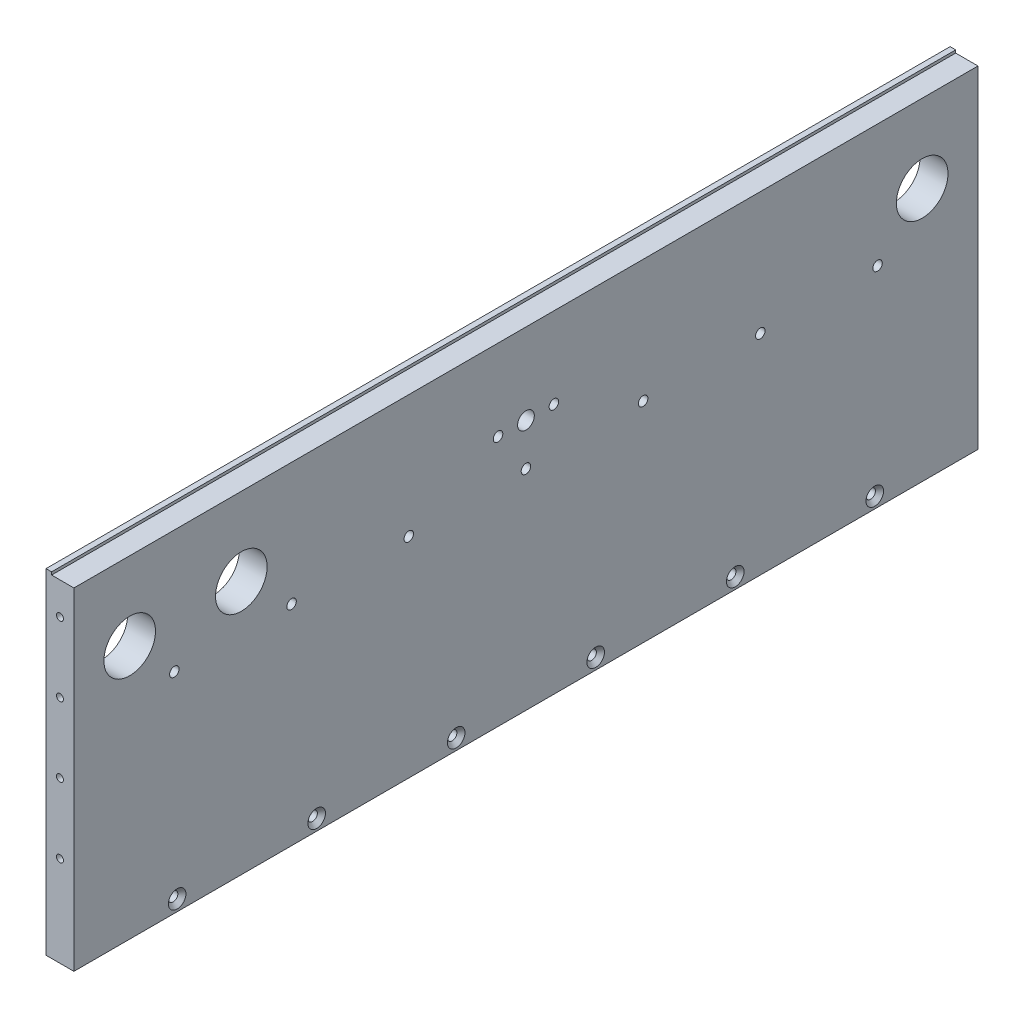
SolidWorks part; units mm, degrees
ref_plane "Front Plane" through (0, 0, 0) normal (0, 0, 1) x (1, 0, 0)
ref_plane "Top Plane" through (0, 0, 0) normal (0, 1, 0) x (1, 0, 0)
ref_plane "Right Plane" through (0, 0, 0) normal (1, 0, 0) x (0, 0, -1)
sketch "Sketch1" plane through (0, 0, 0) normal (1, 0, 0) x (0, 0, -1)
  line L1 (162, -20) -> (-162, -20)
  line L2 (162, -20) -> (162, 20)
  line L3 (162, 20) -> (-162, 20)
  line L4 (-162, -20) -> (-162, 20)
  line L5 (162, -20) -> (-162, 20) construction
  line L6 (162, 20) -> (-162, -20) construction
  point P0 (0, 0)
  dimension "D1" = 40
  dimension "D2" = 324
extrude "Boss-Extrude1" add sketch "Sketch1" along normal blind 10
sketch "Sketch2" plane through (0, 0, 0) normal (-1, 0, 0) x (0, 0, 1)
  line L0 (0, -20) -> (0, -10) construction
  line L1 (162, -20) -> (-162, -20) construction
  line L2 (-10, -20) -> (-10, -10) construction
  point P6 (0, -10)
  point P9 (-10, -10)
  dimension "D1" = 10
  dimension "D2" = 10
  dimension "D3" = 10
hole_wizard "G1/4 Tapped Hole1" positions "3DSketch1" profile "Sketch4" tap size "G1/4" standard "DIN" end condition through all
sketch3d "3DSketch1"
  point P0 (0, -10, 0)
sketch "Sketch4" plane through (0, -10, 0) normal (0, 1, 0) x (0, 0, 1)
  line L0 (0, 0) -> (0, 10)
  line L1 (0, 10) -> (3, 10)
  line L2 (3, 10) -> (3, 0)
  line L5 (3, 0) -> (0, 0)
  line L11 (0, -6.35) -> (0, 107.95) construction
  dimension "Thru Tap Drill Dia." = 6
  dimension "Thru Tap Drill Depth" = 10
cosmetic thread "Hole Thread1" parameters "D2"=13.157
hole_wizard "CSK for M3 Countersunk Flat Head1" positions "3DSketch2" profile "Sketch5" countersink size "M3" standard "BSI" end condition through all
sketch3d "3DSketch2"
  point P0 (0, -10, -10)
sketch "Sketch5" plane through (0, -10, -10) normal (0, 1, 0) x (0, 0, 1)
  line L0 (0, 0) -> (0, 10)
  line L1 (0, 10) -> (1.7, 10)
  line L2 (1.7, 10) -> (1.7, 1.45)
  line L3 (1.7, 1.45) -> (3.15, 0)
  line L5 (3.15, 0) -> (0, 0)
  line L6 (-1.7, 1.45) -> (-3.15, 0) construction
  line L11 (0, -6.35) -> (0, 107.95) construction
  dimension "Thru Hole Dia." = 3.4
  dimension "Thru Hole Depth" = 10
  dimension "Near C'Sink Dia." = 6.3
  dimension "Near C'Sink Angle" = 90
mirror "Mirror1" about plane through (0, 0, 0) normal (0, 0, 1) of "CSK for M3 Countersunk Flat Head1"
sketch "Sketch9" plane through (0, -20, 0) normal (0, -1, 0) x (1, 0, 0)
  line L4 (0, 162) -> (0, -162)
  line L5 (0, -162) -> (10, -162)
  line L6 (10, -162) -> (10, 162)
  line L7 (10, 162) -> (0, 162)
  line L8 (0, 162) -> (0, -162)
  line L9 (0, -162) -> (10, -162)
  line L10 (10, -162) -> (10, 162)
  line L11 (10, 162) -> (0, 162)
  dimension "D1" = 0
extrude "Boss-Extrude2" add sketch "Sketch9" along normal blind 80
sketch "Sketch10" plane through (10, 0, 0) normal (1, 0, 0) x (0, 0, -1)
  line L0 (-125, -96) -> (125, -96) construction
  line L1 (0, -96) -> (0, -100) construction
  line L2 (162, -100) -> (-162, -100) construction
  point P0 (-125, -96)
  point P2 (-75, -96)
  point P4 (-25, -96)
  point P6 (25, -96)
  point P8 (75, -96)
  point P10 (125, -96)
  dimension "D1" = 4
  dimension "D2" = 25
  dimension "D3" = 50
  dimension "D4" = 50
  dimension "D5" = 50
  dimension "D6" = 50
  dimension "D7" = 50
sketch "Sketch11" plane through (0, 0, 162) normal (0, 0, 1) x (1, 0, 0)
  point P0 (5, -67.5)
  point P2 (5, -42.5)
  point P4 (5, -17.5)
  point P6 (5, 7.5)
hole_wizard "CSK for M3 Countersunk Flat Head2" positions "3DSketch3" profile "Sketch12" countersink size "M3" standard "BSI"
sketch3d "3DSketch3"
  point P0 (10, -96, 125)
  point P3 (10, -96, 75)
  point P6 (10, -96, 25)
  point P9 (10, -96, -25)
  point P12 (10, -96, -75)
  point P15 (10, -96, -125)
sketch "Sketch12" plane through (10, -96, 125) normal (0, 1, 0) x (0, 0, -1)
  line L0 (0, 0) -> (0, 12.5215)
  line L1 (0, 12.5215) -> (1.7, 11.5)
  line L2 (1.7, 11.5) -> (1.7, 1.45)
  line L3 (1.7, 1.45) -> (3.15, 0)
  line L5 (3.15, 0) -> (0, 0)
  line L6 (-1.7, 1.45) -> (-3.15, 0) construction
  line L10 (0, 12.5215) -> (-1.7, 11.5) construction
  line L11 (0, -6.35) -> (0, 107.95) construction
  dimension "Hole Dia." = 3.4
  dimension "Hole Depth" = 11.5
  dimension "Near C'Sink Dia." = 6.3
  dimension "Near C'Sink Angle" = 90
  dimension "Drill Angle" = 118
hole_wizard "M3x0.5 Tapped Hole1" positions "3DSketch4" profile "Sketch13" tap size "M3x0.5" standard "BSI"
sketch3d "3DSketch4"
  point P0 (5, 7.5, 162)
  point P3 (5, -17.5, 162)
  point P6 (5, -42.5, 162)
  point P9 (5, -67.5, 162)
sketch "Sketch13" plane through (5, 7.5, 162) normal (1, 0, 0) x (0, -1, 0)
  line L0 (0, 0) -> (0, 12.2511)
  line L1 (0, 12.2511) -> (1.25, 11.5)
  line L2 (1.25, 11.5) -> (1.25, 0)
  line L5 (1.25, 0) -> (0, 0)
  line L10 (0, 12.2511) -> (-1.25, 11.5) construction
  line L11 (0, -6.35) -> (0, 107.95) construction
  dimension "Tap Drill Dia." = 2.5
  dimension "Tap Drill Depth" = 11.5
  dimension "Drill Angle" = 118
cosmetic thread "Hole Thread2" parameters "D1"=10, "D2"=3
cosmetic thread "Hole Thread3" parameters "D1"=10, "D2"=3
cosmetic thread "Hole Thread4" parameters "D1"=10, "D2"=3
cosmetic thread "Hole Thread5" parameters "D1"=10, "D2"=3
mirror "Mirror2" about plane through (0, 0, 0) normal (0, 0, 1) of "M3x0.5 Tapped Hole1"
sketch "Sketch14" plane through (0, 20, 0) normal (0, 1, 0) x (1, 0, 0)
  line L5 (10, 162) -> (0, 162) construction
  line L6 (10, -162) -> (2, -162)
  line L7 (10, -162) -> (10, 162)
  line L8 (10, 162) -> (2, 162)
  line L9 (2, -162) -> (2, 162)
  dimension "D1" = 8
extrude "Cut-Extrude1" cut sketch "Sketch14" against normal blind 1
sketch "Sketch16" plane through (0, 0, 0) normal (-1, 0, 0) x (0, 0, 1)
  line L0 (0, 20) -> (0, -25) construction
  line L1 (-162, 20) -> (162, 20) construction
  line L2 (0, -25) -> (-13.5753, -25) construction
  dimension "D1" = 45
hole_wizard "CSK for M3 Cross Recess Flat Head Screw1" positions "3DSketch5" profile "Sketch17" countersink size "M3" standard "IS" end condition through all
sketch3d "3DSketch5"
  point P0 (0, -25, 0)
sketch "Sketch17" plane through (0, -25, 0) normal (0, 1, 0) x (0, 0, 1)
  line L0 (0, 0) -> (0, 10)
  line L1 (0, 10) -> (1.7, 10)
  line L2 (1.7, 10) -> (1.7, 1.45)
  line L3 (1.7, 1.45) -> (3.15, 0)
  line L5 (3.15, 0) -> (0, 0)
  line L6 (-1.7, 1.45) -> (-3.15, 0) construction
  line L11 (0, -6.35) -> (0, 107.95) construction
  dimension "Thru Hole Dia." = 3.4
  dimension "Thru Hole Depth" = 10
  dimension "Near C'Sink Dia." = 6.3
  dimension "Near C'Sink Angle" = 90
pattern_linear "LPattern1" count 4 spacing 42 along (0, 0, 1) count 4 spacing 42 along (0, 0, -1) of "CSK for M3 Cross Recess Flat Head Screw1"
sketch "Sketch18" plane through (0, 0, 0) normal (-1, 0, 0) x (0, 0, 1)
  line L0 (-162, 20) -> (162, 20) construction
  line L1 (162, 20) -> (162, -100) construction
  line L2 (0, 0) -> (0, 20) construction
  point P0 (142, -9)
  point P6 (102, -9)
  point P9 (-142, -9)
  dimension "D1" = 29
  dimension "D2" = 20
  dimension "D3" = 29
  dimension "D4" = 60
hole_wizard "M20x1.5 Tapped Hole1" positions "3DSketch6" profile "Sketch19" tap size "M20x1.5" standard "BSI" end condition through all
sketch3d "3DSketch6"
  point P0 (0, -9, 142)
  point P3 (0, -9, -142)
  point P6 (0, -9, 102)
sketch "Sketch19" plane through (0, -9, 142) normal (0, 1, 0) x (0, 0, 1)
  line L0 (0, 0) -> (0, 10)
  line L1 (0, 10) -> (9.25, 10)
  line L2 (9.25, 10) -> (9.25, 0)
  line L5 (9.25, 0) -> (0, 0)
  line L11 (0, -6.35) -> (0, 107.95) construction
  dimension "Thru Tap Drill Dia." = 18.5
  dimension "Thru Tap Drill Depth" = 10
cosmetic thread "Hole Thread6" parameters "D2"=20
cosmetic thread "Hole Thread7" parameters "D2"=20
cosmetic thread "Hole Thread8" parameters "D2"=20
